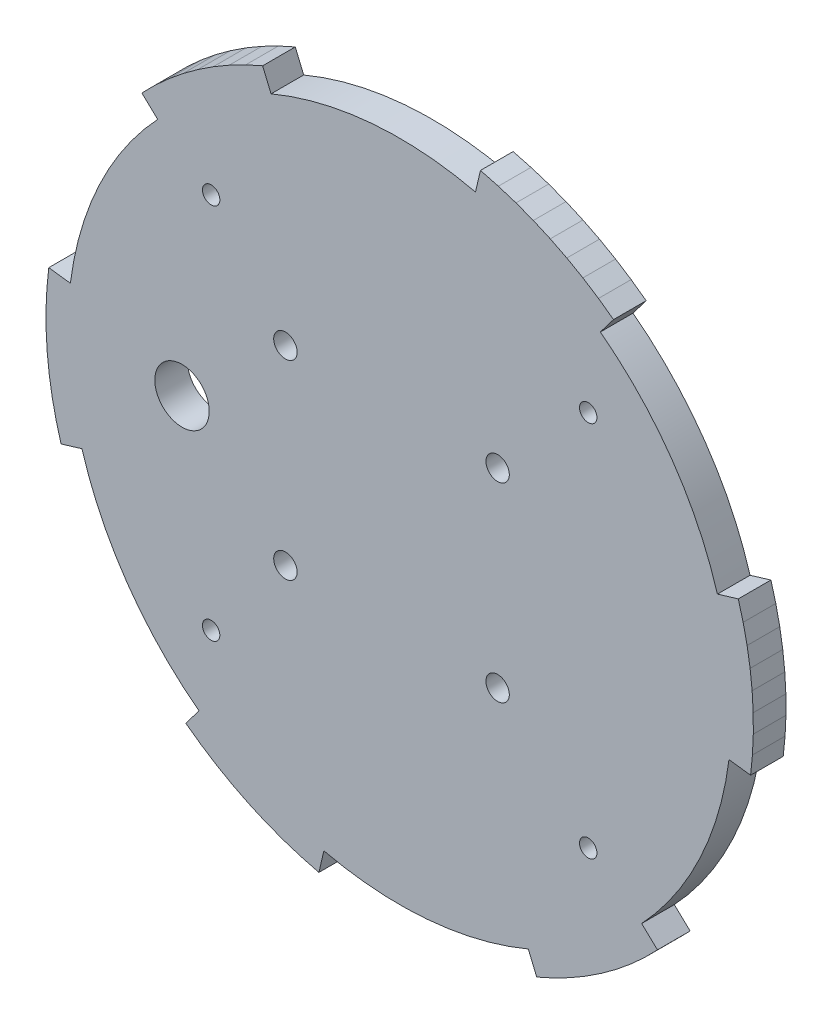
SolidWorks part; units mm, degrees
ref_plane "Front Plane" through (0, 0, 0) normal (0, 0, 1) x (1, 0, 0)
ref_plane "Top Plane" through (0, 0, 0) normal (0, 1, 0) x (1, 0, 0)
ref_plane "Right Plane" through (0, 0, 0) normal (1, 0, 0) x (0, 0, -1)
sketch "草圖1" plane through (0, 0, 0) normal (0, 0, 1) x (1, 0, 0)
  circle A0 centre (0, 0) radius 61
  circle A1 centre (34.6482, 34.6482) radius 1.6
  circle A2 centre (-34.6482, 34.6482) radius 1.6
  circle A3 centre (-34.6482, -34.6482) radius 1.6
  circle A4 centre (34.6482, -34.6482) radius 1.6
  circle A5 centre (-21, 17.5) radius 2.15
  circle A6 centre (-21, -17.5) radius 2.15
  circle A7 centre (18, 17.5) radius 2.15
  circle A8 centre (18, -17.5) radius 2.15
  circle A9 centre (-40, 0) radius 5
extrude "填料-伸長1" add sketch "草圖1" along normal blind 6
sketch "草圖2" plane through (0, 0, 0) normal (0, 0, 1) x (1, 0, 0)
  line L0 (64.4875, -8.1467) -> (64.8254, -4.7605)
  line L1 (64.8254, -4.7605) -> (64.9857, -1.3613)
  line L2 (64.9857, -1.3613) -> (64.9679, 2.0417)
  line L3 (64.9679, 2.0417) -> (64.772, 5.4391)
  line L4 (64.772, 5.4391) -> (64.3986, 8.8215)
  line L5 (64.3986, 8.8215) -> (63.8487, 12.1798)
  line L6 (63.8487, 12.1798) -> (63.1237, 15.5047)
  line L7 (63.1237, 15.5047) -> (62.2258, 18.7871)
  line L8 (62.2258, 18.7871) -> (57.9178, 17.4864)
  line L9 (57.9178, 17.4864) -> (58.7536, 14.4313)
  line L10 (58.7536, 14.4313) -> (59.4284, 11.3366)
  line L11 (59.4284, 11.3366) -> (59.9402, 8.2108)
  line L12 (59.9402, 8.2108) -> (60.2878, 5.0625)
  line L13 (60.2878, 5.0625) -> (60.4701, 1.9004)
  line L14 (60.4701, 1.9004) -> (60.4867, -1.267)
  line L15 (60.4867, -1.267) -> (60.3375, -4.4309)
  line L16 (60.3375, -4.4309) -> (60.0229, -7.5827)
  line L17 (60.0229, -7.5827) -> (64.4875, -8.1467)
  line L18 (39.2989, 51.7744) -> (36.5354, 53.7602)
  line L19 (36.5354, 53.7602) -> (33.6718, 55.5987)
  line L20 (33.6718, 55.5987) -> (30.7158, 57.2847)
  line L21 (30.7158, 57.2847) -> (27.6757, 58.8138)
  line L22 (27.6757, 58.8138) -> (24.5597, 60.1816)
  line L23 (24.5597, 60.1816) -> (21.3763, 61.3845)
  line L24 (21.3763, 61.3845) -> (18.1344, 62.4191)
  line L25 (18.1344, 62.4191) -> (14.8428, 63.2826)
  line L26 (14.8428, 63.2826) -> (13.8152, 58.9015)
  line L27 (13.8152, 58.9015) -> (16.879, 58.0978)
  line L28 (16.879, 58.0978) -> (19.8964, 57.1348)
  line L29 (19.8964, 57.1348) -> (22.8594, 56.0152)
  line L30 (22.8594, 56.0152) -> (25.7596, 54.742)
  line L31 (25.7596, 54.742) -> (28.5893, 53.3189)
  line L32 (28.5893, 53.3189) -> (31.3406, 51.7495)
  line L33 (31.3406, 51.7495) -> (34.006, 50.0384)
  line L34 (34.006, 50.0384) -> (36.5782, 48.1901)
  line L35 (36.5782, 48.1901) -> (39.2989, 51.7744)
  line L36 (-25.1885, 59.9211) -> (-28.29, 58.5207)
  line L37 (-28.29, 58.5207) -> (-31.314, 56.9599)
  line L38 (-31.314, 56.9599) -> (-34.2521, 55.243)
  line L39 (-34.2521, 55.243) -> (-37.0964, 53.3747)
  line L40 (-37.0964, 53.3747) -> (-39.839, 51.3601)
  line L41 (-39.839, 51.3601) -> (-42.4723, 49.2047)
  line L42 (-42.4723, 49.2047) -> (-44.9893, 46.9144)
  line L43 (-44.9893, 46.9144) -> (-47.383, 44.4956)
  line L44 (-47.383, 44.4956) -> (-44.1026, 41.4151)
  line L45 (-44.1026, 41.4151) -> (-41.8747, 43.6665)
  line L46 (-41.8747, 43.6665) -> (-39.5319, 45.7982)
  line L47 (-39.5319, 45.7982) -> (-37.0809, 47.8044)
  line L48 (-37.0809, 47.8044) -> (-34.5282, 49.6795)
  line L49 (-34.5282, 49.6795) -> (-31.8808, 51.4185)
  line L50 (-31.8808, 51.4185) -> (-29.1461, 53.0166)
  line L51 (-29.1461, 53.0166) -> (-26.3315, 54.4693)
  line L52 (-26.3315, 54.4693) -> (-23.4447, 55.7727)
  line L53 (-23.4447, 55.7727) -> (-25.1885, 59.9211)
  line L54 (-64.4875, 8.1467) -> (-64.8254, 4.7605)
  line L55 (-64.8254, 4.7605) -> (-64.9857, 1.3613)
  line L56 (-64.9857, 1.3613) -> (-64.9679, -2.0417)
  line L57 (-64.9679, -2.0417) -> (-64.772, -5.4391)
  line L58 (-64.772, -5.4391) -> (-64.3986, -8.8215)
  line L59 (-64.3986, -8.8215) -> (-63.8487, -12.1798)
  line L60 (-63.8487, -12.1798) -> (-63.1237, -15.5047)
  line L61 (-63.1237, -15.5047) -> (-62.2258, -18.7871)
  line L62 (-62.2258, -18.7871) -> (-57.9178, -17.4864)
  line L63 (-57.9178, -17.4864) -> (-58.7536, -14.4313)
  line L64 (-58.7536, -14.4313) -> (-59.4284, -11.3366)
  line L65 (-59.4284, -11.3366) -> (-59.9402, -8.2108)
  line L66 (-59.9402, -8.2108) -> (-60.2878, -5.0625)
  line L67 (-60.2878, -5.0625) -> (-60.4701, -1.9004)
  line L68 (-60.4701, -1.9004) -> (-60.4867, 1.267)
  line L69 (-60.4867, 1.267) -> (-60.3375, 4.4309)
  line L70 (-60.3375, 4.4309) -> (-60.0229, 7.5827)
  line L71 (-60.0229, 7.5827) -> (-64.4875, 8.1467)
  line L72 (-39.2989, -51.7744) -> (-36.5354, -53.7602)
  line L73 (-36.5354, -53.7602) -> (-33.6718, -55.5987)
  line L74 (-33.6718, -55.5987) -> (-30.7158, -57.2847)
  line L75 (-30.7158, -57.2847) -> (-27.6757, -58.8138)
  line L76 (-27.6757, -58.8138) -> (-24.5597, -60.1816)
  line L77 (-24.5597, -60.1816) -> (-21.3763, -61.3845)
  line L78 (-21.3763, -61.3845) -> (-18.1344, -62.4191)
  line L79 (-18.1344, -62.4191) -> (-14.8428, -63.2826)
  line L80 (-14.8428, -63.2826) -> (-13.8152, -58.9015)
  line L81 (-13.8152, -58.9015) -> (-16.879, -58.0978)
  line L82 (-16.879, -58.0978) -> (-19.8964, -57.1348)
  line L83 (-19.8964, -57.1348) -> (-22.8594, -56.0152)
  line L84 (-22.8594, -56.0152) -> (-25.7596, -54.742)
  line L85 (-25.7596, -54.742) -> (-28.5893, -53.3189)
  line L86 (-28.5893, -53.3189) -> (-31.3406, -51.7495)
  line L87 (-31.3406, -51.7495) -> (-34.006, -50.0384)
  line L88 (-34.006, -50.0384) -> (-36.5782, -48.1901)
  line L89 (-36.5782, -48.1901) -> (-39.2989, -51.7744)
  line L90 (25.1885, -59.9211) -> (28.29, -58.5207)
  line L91 (28.29, -58.5207) -> (31.314, -56.9599)
  line L92 (31.314, -56.9599) -> (34.2521, -55.243)
  line L93 (34.2521, -55.243) -> (37.0964, -53.3747)
  line L94 (37.0964, -53.3747) -> (39.839, -51.3601)
  line L95 (39.839, -51.3601) -> (42.4723, -49.2047)
  line L96 (42.4723, -49.2047) -> (44.9893, -46.9144)
  line L97 (44.9893, -46.9144) -> (47.383, -44.4956)
  line L98 (47.383, -44.4956) -> (44.1026, -41.4151)
  line L99 (44.1026, -41.4151) -> (41.8747, -43.6665)
  line L100 (41.8747, -43.6665) -> (39.5319, -45.7982)
  line L101 (39.5319, -45.7982) -> (37.0809, -47.8044)
  line L102 (37.0809, -47.8044) -> (34.5282, -49.6795)
  line L103 (34.5282, -49.6795) -> (31.8808, -51.4185)
  line L104 (31.8808, -51.4185) -> (29.1461, -53.0166)
  line L105 (29.1461, -53.0166) -> (26.3315, -54.4693)
  line L106 (26.3315, -54.4693) -> (23.4447, -55.7727)
  line L107 (23.4447, -55.7727) -> (25.1885, -59.9211)
extrude "填料-伸長2" add sketch "草圖2" along normal blind 6
sketch "草圖3" plane through (0, 0, 0) normal (0, 0, 1) x (1, 0, 0)
  circle A0 centre (0, 15) radius 5
  circle A1 centre (0, -15) radius 5
extrude "填料-伸長3" add sketch "草圖3" against normal blind 6
sketch "草圖4" plane through (0, 0, 0) normal (0, 1, 0) x (1, 0, 0)
  line L0 (-20, 6) -> (20, 6) construction
  circle A0 centre (0, 21) radius 5
revolve "旋轉1" add sketch "草圖4" angle 90 about L0 other way angle 90
